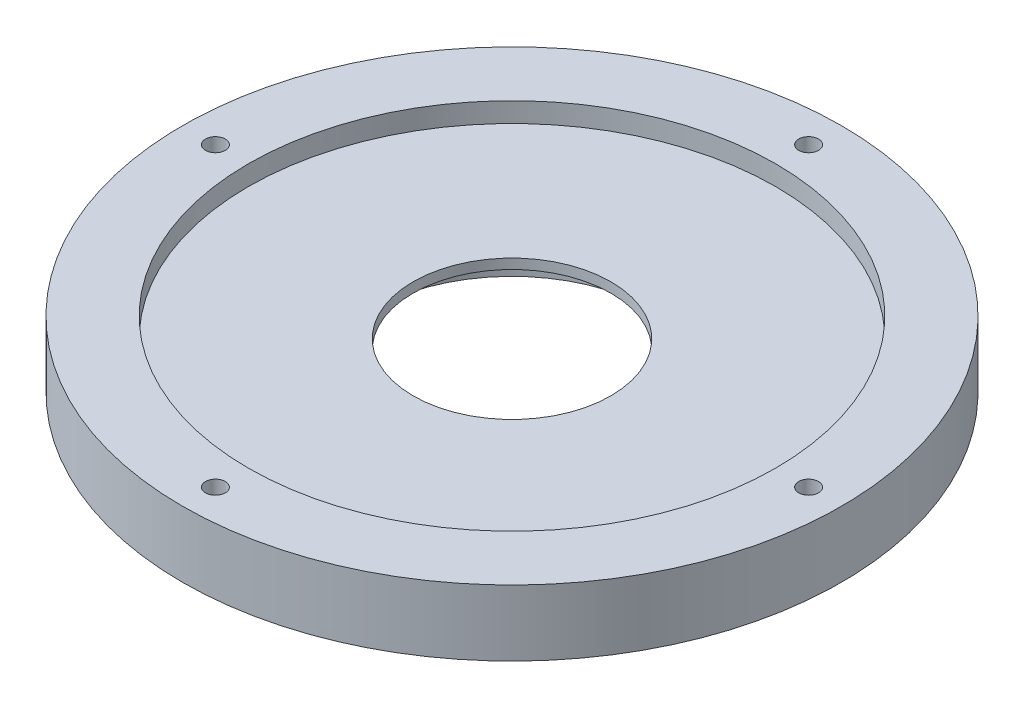
SolidWorks part; units mm, degrees
ref_plane "前视基准面" through (0, 0, 0) normal (0, 0, 1) x (1, 0, 0)
ref_plane "上视基准面" through (0, 0, 0) normal (0, 1, 0) x (1, 0, 0)
ref_plane "右视基准面" through (0, 0, 0) normal (1, 0, 0) x (0, 0, -1)
other "Configuration Table"
sketch "草图2" plane through (0, 0, 0) normal (0, 1, 0) x (1, 0, 0)
  circle A0 centre (0, 0) radius 100
  circle A1 centre (0, 0) radius 90 construction
  circle A2 centre (0, 90) radius 3
  circle A3 centre (90, 0) radius 3
  circle A4 centre (0, -90) radius 3
  circle A5 centre (-90, 0) radius 3
  circle A6 centre (0, 0) radius 30
  dimension "D1" = 4
extrude "凸台-拉伸1" add sketch "草图2" along normal blind 20
sketch "草图3" plane through (0, 0, 0) normal (0, -1, 0) x (1, 0, 0)
  circle A0 centre (0, 0) radius 43
  dimension "D1" = 86
extrude "切除-拉伸1" cut sketch "草图3" against normal blind 11
sketch "草图4" plane through (0, 20, 0) normal (0, 1, 0) x (1, 0, 0)
  circle A0 centre (0, 0) radius 80
extrude "切除-拉伸2" cut sketch "草图4" against normal blind 6
